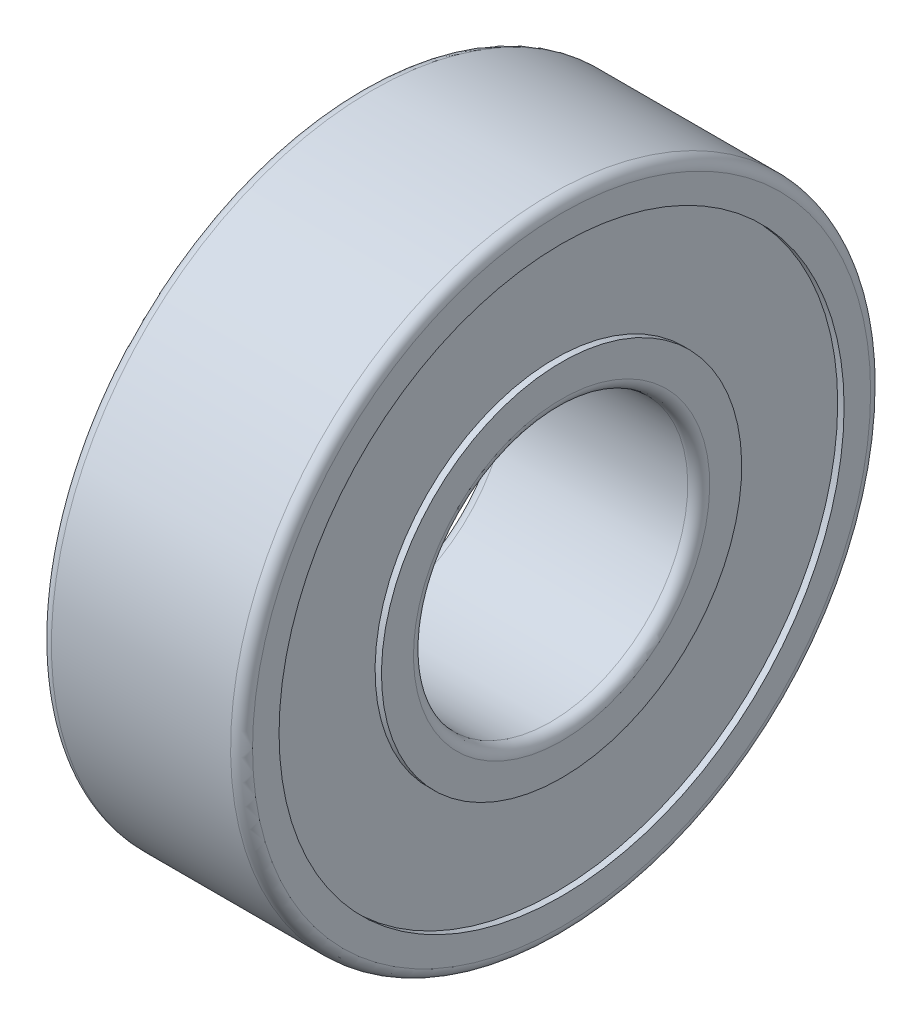
SolidWorks part; units mm, degrees
ref_plane "Front Plane" through (0, 0, 0) normal (0, 0, 1) x (1, 0, 0)
ref_plane "Top Plane" through (0, 0, 0) normal (0, 1, 0) x (1, 0, 0)
ref_plane "Right Plane" through (0, 0, 0) normal (1, 0, 0) x (0, 0, -1)
sketch "Sketch1" plane through (0, 0, 0) normal (0, 0, 1) x (1, 0, 0)
  line L0 (0, 0) -> (11, 0) construction
  line L1 (0, 17.5) -> (11, 17.5)
  line L2 (11, 17.5) -> (11, 15.45)
  line L3 (11, 15.45) -> (10.65, 15.45)
  line L4 (10.65, 15.45) -> (10.65, 9.85)
  line L5 (10.65, 9.85) -> (11, 9.85)
  line L6 (11, 9.85) -> (11, 7.5)
  line L7 (11, 7.5) -> (0, 7.5)
  line L8 (0, 7.5) -> (0, 9.85)
  line L9 (0, 9.85) -> (0.35, 9.85)
  line L10 (0.35, 9.85) -> (0.35, 15.45)
  line L11 (0.35, 15.45) -> (0, 15.45)
  line L12 (0, 15.45) -> (0, 17.5)
  dimension "D_s" = 15
  dimension "B" = 11
  dimension "D" = 35
  dimension "MSM_5" = 10.3
  dimension "MSM_3" = 19.7
  dimension "MSM_4" = 30.9
revolve "Revolve1" add sketch "Sketch1" angle 360 about L0
fillet "Fillet1" radius 0.6 4 edges at (0, -7.5, 0) (11, -7.5, 0) (0, -17.5, 0) (11, -17.5, 0)
